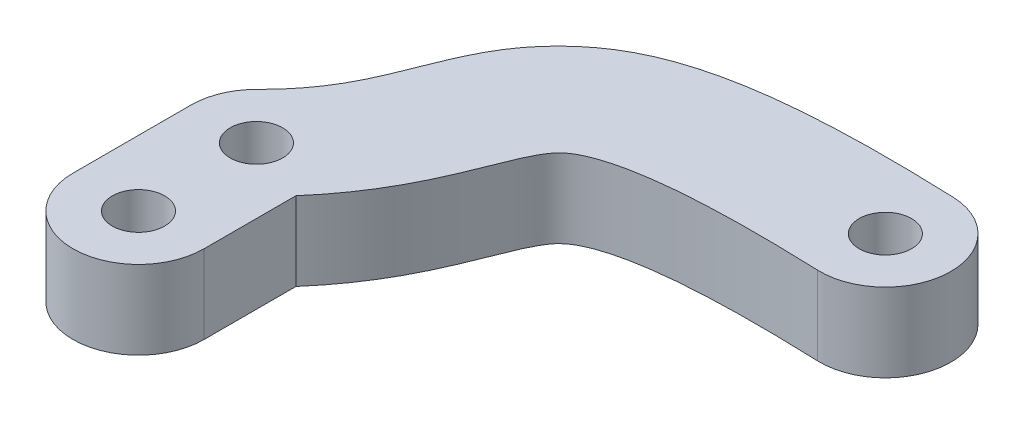
SolidWorks part; units mm, degrees
ref_plane "Front Plane" through (0, 0, 0) normal (0, 0, 1) x (1, 0, 0)
ref_plane "Top Plane" through (0, 0, 0) normal (0, 1, 0) x (1, 0, 0)
ref_plane "Right Plane" through (0, 0, 0) normal (1, 0, 0) x (0, 0, -1)
sketch "Sketch1" plane through (0, 0, 0) normal (0, 1, 0) x (1, 0, 0)
  line L0 (0, 0) -> (0, -4.5) construction
  line L1 (2.5, 0) -> (2.5, -4.5)
  line L2 (-2.5, 0) -> (-2.5, -4.5)
  arc A0 (1.7544, -1.7811) -> (-1.7544, 1.7811) centre (0, 0) cw
  arc A1 (14.9055, 6.5018) -> (15.0945, 11.4982) centre (15, 9) ccw
  arc A5 (2.5, 0) -> (-2.5, 0) centre (0, 0) ccw
  arc A6 (-2.5, -4.5) -> (2.5, -4.5) centre (0, -4.5) ccw
  spline S0 degree 3 poles (0, 0) (5.4167, 5.3355) (0.0171, 9.5666) (15, 9) knots 0 0 0 0 1 1 1 1
  spline S1 degree 1 poles (1.7544, -1.7811) (14.9055, 6.5018) knots 0 0 1 1 construction
  spline S2 degree 3 poles (1.7544, -1.7811) (1.9515, -1.5869) (2.3421, -1.1798) (3.0203, -0.3855) (3.7258, 0.6037) (4.3637, 1.7355) (4.9949, 3.1169) (5.5044, 4.5036) (5.8787, 5.1992) (6.1258, 5.4759) (6.3728, 5.6723) (6.8302, 5.9083) (7.6117, 6.1567) (8.7718, 6.3697) (10.0803, 6.4895) (11.3439, 6.5408) (12.4087, 6.5551) (13.575, 6.5445) (14.4721, 6.5182) (14.9055, 6.5018) knots 0 0 0 0 0.03125 0.0625 0.125 0.1875 0.25 0.375 0.5 0.5625 0.625 0.6875 0.75 0.8125 0.875 0.90625 0.9375 0.96875 1 1 1 1
  spline S3 degree 1 poles (-1.7544, 1.7811) (15.0945, 11.4982) knots 0 0 1 1 construction
  spline S4 degree 3 poles (-1.7544, 1.7811) (-1.6243, 1.9091) (-1.3636, 2.1809) (-0.934, 2.6849) (-0.5005, 3.2932) (-0.1016, 3.9991) (0.3408, 4.9579) (0.8219, 6.2556) (1.7143, 8.1881) (3.6559, 10.0809) (5.9334, 10.9409) (8.1465, 11.3365) (10.0801, 11.51) (11.9786, 11.5595) (13.6772, 11.5437) (14.6309, 11.5157) (15.0945, 11.4982) knots 0 0 0 0 0.03125 0.0625 0.125 0.1875 0.25 0.375 0.5 0.625 0.75 0.8125 0.875 0.9375 0.96875 1 1 1 1
  point P12 (0, -2.25)
  dimension "D1" = 9
  dimension "D2" = 4.5
  dimension "D3" = 15
  dimension "D4" = 2.5
  dimension "D5" = 2.5
extrude "Boss-Extrude1" add sketch "Sketch1" along normal blind 3
sketch "Sketch2" plane through (0, 3, 0) normal (0, 1, 0) x (1, 0, 0)
  circle A0 centre (0, 0) radius 1
  circle A1 centre (0, -4.5) radius 1
  circle A2 centre (15, 9) radius 1
  dimension "D1" = 2
  dimension "D2" = 2
extrude "Cut-Extrude1" cut sketch "Sketch2" against normal through all
